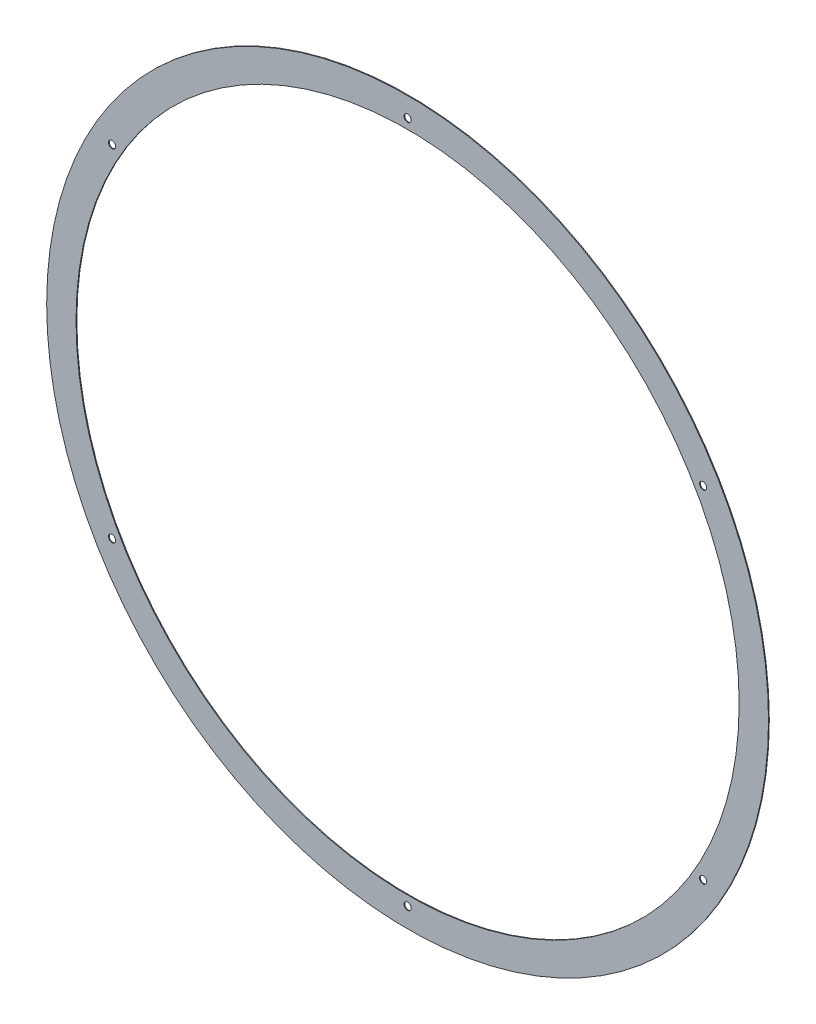
SolidWorks part; units mm, degrees
material "AISI 304"
ref_plane "Front Plane" through (0, 0, 0) normal (0, 0, 1) x (1, 0, 0)
ref_plane "Top Plane" through (0, 0, 0) normal (0, 1, 0) x (1, 0, 0)
ref_plane "Right Plane" through (0, 0, 0) normal (1, 0, 0) x (0, 0, -1)
sketch "Sketch1" plane through (0, 0, 0) normal (0, 0, 1) x (1, 0, 0)
  circle A0 centre (-20.0737, -8.1031) radius 114.3
  circle A1 centre (-113.6586, 45.9281) radius 1.1303
  circle A2 centre (-20.0737, -8.1031) radius 105
  circle A3 centre (-20.0737, 99.9594) radius 1.1303
  circle A4 centre (73.5112, 45.9281) radius 1.1303
  circle A5 centre (73.5112, -62.1344) radius 1.1303
  circle A6 centre (-20.0737, -116.1656) radius 1.1303
  circle A7 centre (-113.6586, -62.1344) radius 1.1303
  dimension "D1" = 210
  dimension "D2" = 228.6
  dimension "D3" = 2.2606
extrude "Boss-Extrude1" add sketch "Sketch1" along normal blind 0.254 contours A0 A7 A6 A5 A4 A3 A2 A1
